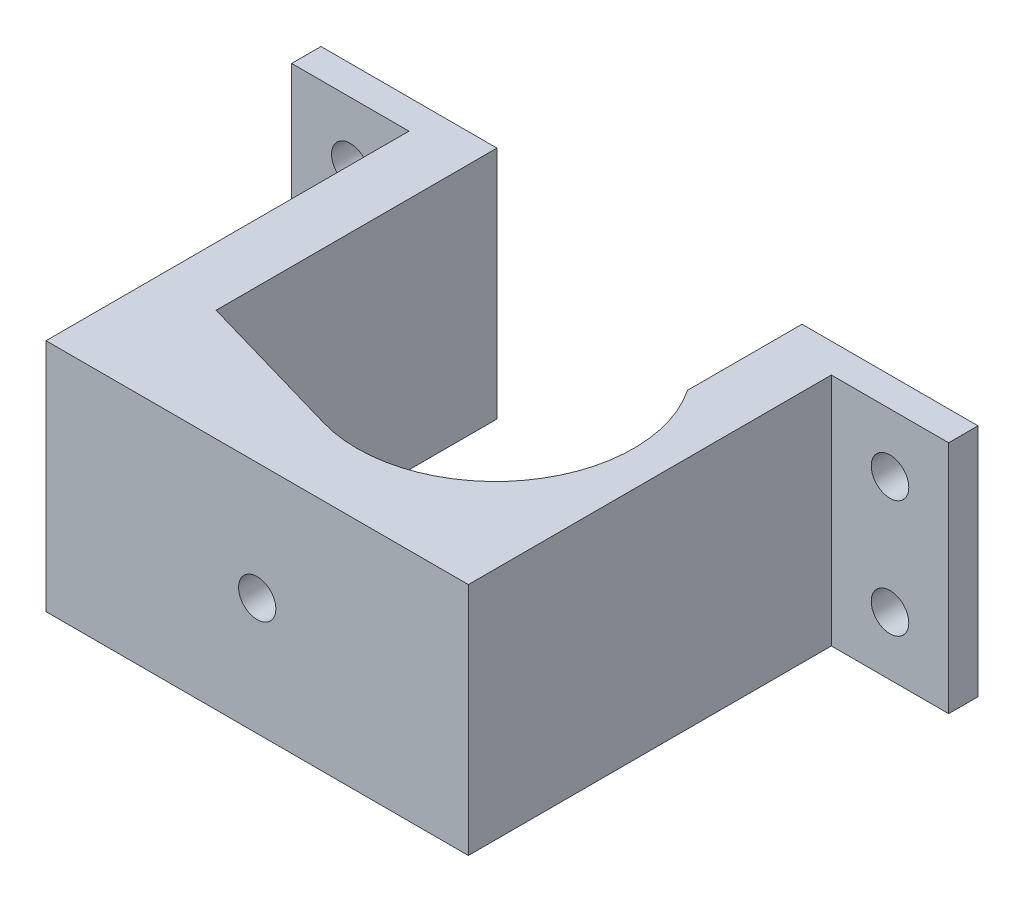
SolidWorks part; units mm, degrees
ref_plane "Front Plane" through (0, 0, 0) normal (0, 0, 1) x (1, 0, 0)
ref_plane "Top Plane" through (0, 0, 0) normal (0, 1, 0) x (1, 0, 0)
ref_plane "Right Plane" through (0, 0, 0) normal (1, 0, 0) x (0, 0, -1)
sketch "Sketch1" plane through (0, 0, 0) normal (0, 1, 0) x (1, 0, 0)
  line L0 (-20.574, -9.6521) -> (-4.162, -14.3967)
  line L1 (-4.1621, 14.3967) -> (-20.574, 9.652) construction
  line L2 (-20.574, 9.652) -> (-20.574, -9.6521)
  line L3 (-39.624, 20.7467) -> (-20.574, 20.7467)
  line L4 (-39.624, 20.7467) -> (-39.624, 17.5717)
  line L6 (12.446, 20.7467) -> (31.496, 20.7467)
  line L7 (-39.624, 17.5717) -> (-26.924, 17.5717)
  line L9 (-26.924, 17.5717) -> (-26.924, -12.8271)
  line L10 (31.496, 20.7467) -> (31.496, 17.5717)
  line L11 (31.496, 17.5717) -> (18.796, 17.5717)
  line L12 (18.796, 17.5717) -> (18.796, -12.8271)
  line L13 (-20.574, 9.652) -> (-20.574, 20.7467)
  line L14 (12.446, 20.7467) -> (12.446, 8.3478)
  line L15 (18.796, -12.8271) -> (18.796, -21.7171)
  line L16 (18.796, -21.7171) -> (-26.924, -21.7171)
  line L17 (-26.924, -21.7171) -> (-26.924, -12.8271)
  arc A0 (-4.162, -14.3967) -> (12.446, 8.3478) centre (0, 0) ccw
  arc A1 (-26.924, -12.8271) -> (18.796, -12.8271) centre (-4.064, 25.294) ccw construction
  arc A2 (12.446, 8.3478) -> (-4.1621, 14.3967) centre (0, 0) ccw construction
  point P6 (12.446, 14.5473)
  point P16 (21.971, 20.7467)
  dimension "D2" = 14.9863
  dimension "D14" = 6.35
  dimension "D10" = 44.45
  dimension "D1" = 19.3041
  dimension "D3" = 16.4119
  dimension "D4" = 106.124
  dimension "D5" = 20.574
  dimension "D6" = 106.125
  dimension "D7" = 6.35
  dimension "D8" = 6.35
  dimension "D9" = 3.175
  dimension "D11" = 12.7
  dimension "D12" = 3.175
  dimension "D13" = 33.02
  dimension "D15" = 8.89
extrude "Boss-Extrude1" add sketch "Sketch1" along normal blind 25.4
sketch "Sketch2" plane through (0, 0, -17.5717) normal (0, 0, 1) x (1, 0, 0)
  line L0 (-39.624, 0) -> (-26.924, 0) construction
  line L1 (-39.624, 25.4) -> (-39.624, 0) construction
  line L2 (-39.624, 25.4) -> (-26.924, 25.4) construction
  line L3 (31.496, 25.4) -> (31.496, 0) construction
  circle A0 centre (-33.274, 19.05) radius 2.032
  circle A1 centre (-33.274, 6.35) radius 2.032
  circle A2 centre (25.146, 19.05) radius 2.032
  circle A3 centre (25.146, 6.35) radius 2.032
  dimension "D5" = 4.064
  dimension "D1" = 6.35
  dimension "D2" = 6.35
  dimension "D3" = 6.35
  dimension "D4" = 6.35
extrude "Cut-Extrude1" cut sketch "Sketch2" against normal through all
sketch "Sketch3" plane through (0, 0, 21.7171) normal (0, 0, 1) x (1, 0, 0)
  line L0 (-26.924, 25.4) -> (18.796, 25.4) construction
  line L1 (-26.924, 25.4) -> (-26.924, 0) construction
  circle A0 centre (-4.064, 12.7) radius 1.905
  dimension "D3" = 3.81
  dimension "D1" = 12.7
  dimension "D2" = 22.86
hole_wizard "#10-32 Tapped Hole1" positions "Sketch4" profile "Sketch5" tap size "#10-32" standard "ANSI Inch" end condition through all
sketch "Sketch4" plane through (0, 0, 21.7171) normal (0, 0, 1) x (1, 0, 0)
  point P0 (-4.064, 12.7)
sketch "Sketch5" plane through (-4.064, 12.7, 21.7171) normal (1, 0, 0) x (0, -1, 0)
  line L0 (0, 0) -> (0, 42.4638)
  line L1 (0, 42.4638) -> (2.0193, 42.4638)
  line L2 (2.0193, 42.4638) -> (2.0193, 0)
  line L5 (2.0193, 0) -> (0, 0)
  line L11 (0, -6.35) -> (0, 107.95) construction
  dimension "Thru Tap Drill Dia." = 4.0386
  dimension "Thru Tap Drill Depth" = 42.4638
cosmetic thread "Hole Thread1" parameters "D2"=4.826
